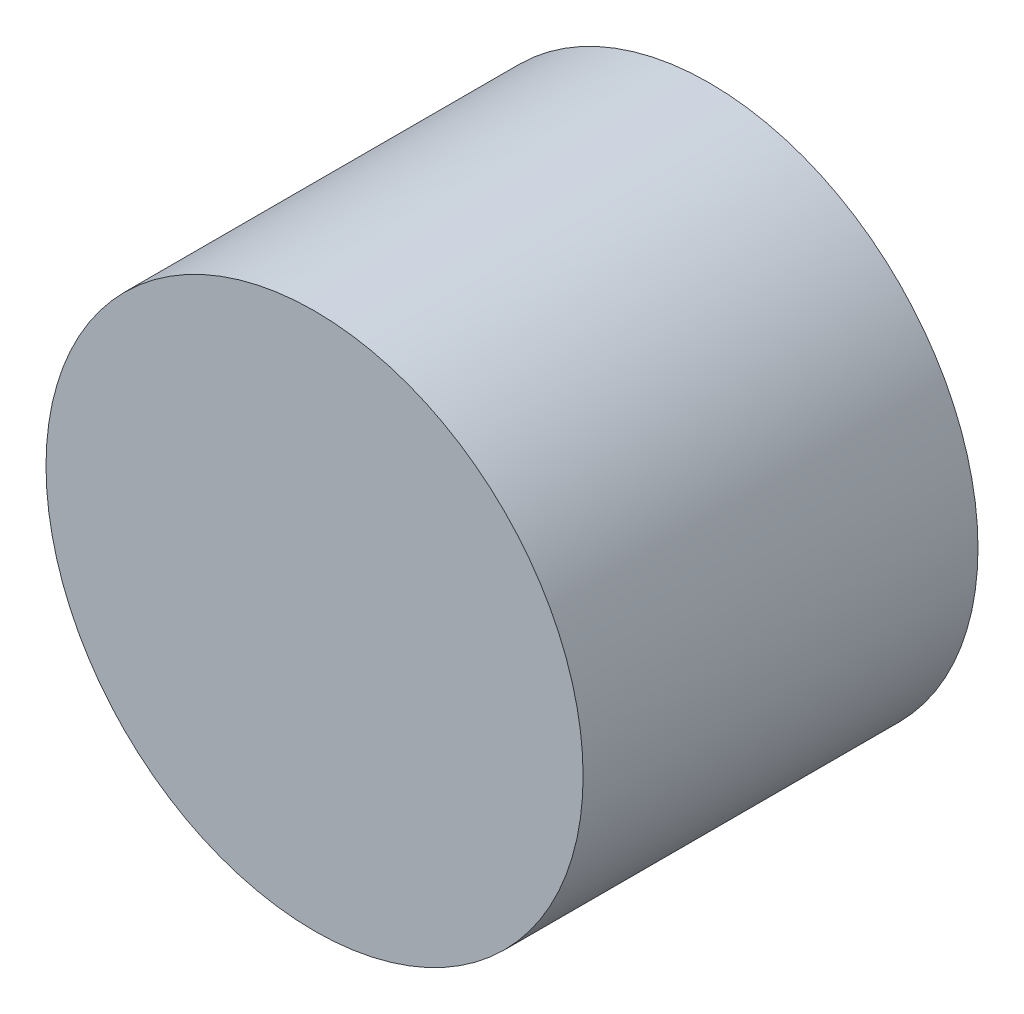
SolidWorks part; units mm, degrees
material "authored material"
ref_plane "Front Plane" through (0, 0, 0) normal (0, 0, 1) x (1, 0, 0)
ref_plane "Top Plane" through (0, 0, 0) normal (0, 1, 0) x (1, 0, 0)
ref_plane "Right Plane" through (0, 0, 0) normal (1, 0, 0) x (0, 0, -1)
sketch "Sketch1" plane through (0, 0, 0) normal (0, 0, 1) x (1, 0, 0)
  circle A0 centre (6.787, -3.953) radius 11.147
  dimension "D1" = 22.294
extrude "Boss-Extrude1" add sketch "Sketch1" along normal blind 16.391
